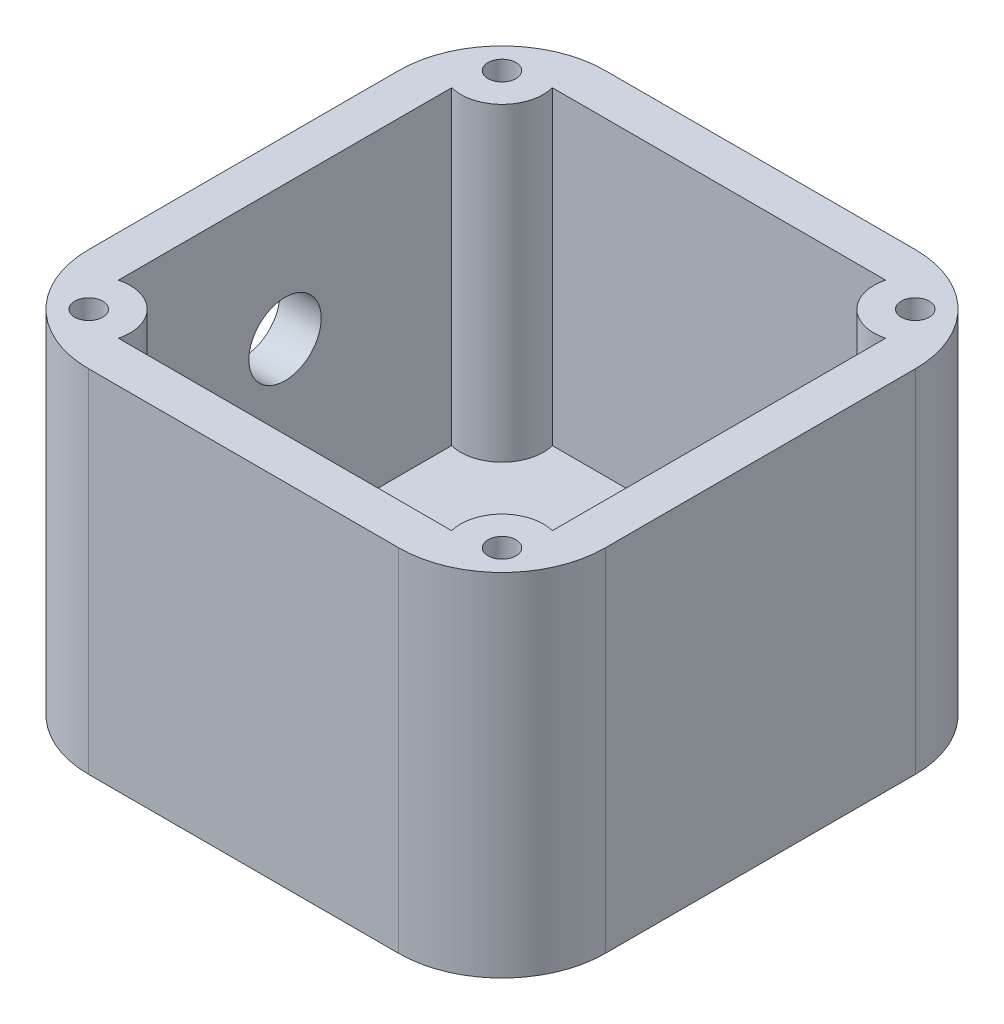
SolidWorks part; units mm, degrees
ref_plane "Front Plane" through (0, 0, 0) normal (0, 0, 1) x (1, 0, 0)
ref_plane "Top Plane" through (0, 0, 0) normal (0, 1, 0) x (1, 0, 0)
ref_plane "Right Plane" through (0, 0, 0) normal (1, 0, 0) x (0, 0, -1)
sketch "Sketch1" plane through (0, 0, 0) normal (0, 1, 0) x (1, 0, 0)
  line L1 (-21, 21) -> (21, 21)
  line L2 (-21, 21) -> (-21, -21)
  line L3 (-21, -21) -> (21, -21)
  line L4 (21, 21) -> (21, -21)
  line L5 (-21, 21) -> (21, -21) construction
  line L6 (-21, -21) -> (21, 21) construction
  point P0 (0, 0)
  dimension "D1" = 42
  dimension "D2" = 42
extrude "Boss-Extrude2" add sketch "Sketch1" along normal blind 30
shell "Shell1" thickness 4
sketch "Sketch2" plane through (0, -4, 0) normal (0, -1, 0) x (-1, 0, 0)
  circle A0 centre (0, 0) radius 6.75
  point P0 (0, 0)
sketch "Sketch3" plane through (0, 0, 0) normal (1, 0, 0) x (0, 0, -1)
  line L0 (-25, 30) -> (-25, -4) construction
  line L1 (-25, 30) -> (25, 30) construction
  circle A0 centre (0, 17) radius 3.5
  point P0 (-1.6703, 16.6909)
  point P7 (0, 30)
  dimension "D1" = 25
  dimension "D2" = 13
extrude "Cut-Extrude1" cut sketch "Sketch3" against normal blind 30
extrude "Cut-Extrude2" cut sketch "Sketch2" against normal blind 30
sketch "Sketch5" plane through (0, -4, 0) normal (0, -1, 0) x (-1, 0, 0)
  line L0 (25, -25) -> (-25, -25) construction
  line L1 (25, 25) -> (25, -25) construction
  line L2 (-25, -25) -> (-25, 25) construction
  line L3 (-25, 25) -> (25, 25) construction
  circle A0 centre (20, -20) radius 4
  circle A1 centre (-20, -20) radius 4
  circle A2 centre (-20, 20) radius 4
  circle A3 centre (20, 20) radius 4
  point P0 (20, 20)
  dimension "D1" = 5
  dimension "D3" = 5
  dimension "D2" = 5
  dimension "D4" = 5
extrude "Boss-Extrude3" add sketch "Sketch5" against normal blind 34
hole_wizard "#6-32 Tapped Hole6" positions "3DSketch6" profile "Sketch11" tap size "#6-32" standard "ANSI Inch"
sketch3d "3DSketch6"
  line L0 (-20, 30, -20) -> (-20, 0, -20) construction
  line L1 (20, 30, -20) -> (20, 0, -20) construction
  line L2 (20, 30, 20) -> (20, 0, 20) construction
  line L3 (-20, 30, 20) -> (-20, 0, 20) construction
  point P0 (-20, 30, -20)
  point P4 (20, 30, -20)
  point P8 (20, 30, 20)
  point P12 (-20, 30, 20)
sketch "Sketch11" plane through (-20, 30, -20) normal (1, 0, 0) x (0, 0, 1)
  line L0 (0, 0) -> (0, 11.7827)
  line L1 (0, 11.7827) -> (1.3525, 10.97)
  line L2 (1.3525, 10.97) -> (1.3525, 0)
  line L5 (1.3525, 0) -> (0, 0)
  line L10 (0, 11.7827) -> (-1.3525, 10.97) construction
  line L11 (0, -6.35) -> (0, 107.95) construction
  dimension "Tap Drill Dia." = 2.7051
  dimension "Tap Drill Depth" = 10.97
  dimension "Drill Angle" = 118
cosmetic thread "Hole Thread21" parameters "D1"=7.01, "D2"=3.5052
cosmetic thread "Hole Thread22" parameters "D1"=7.01, "D2"=3.5052
cosmetic thread "Hole Thread23" parameters "D1"=7.01, "D2"=3.5052
cosmetic thread "Hole Thread24" parameters "D1"=7.01, "D2"=3.5052
fillet "Fillet3" radius 10 4 edges at (-25, 13, 25) (25, 13, 25) (25, 13, -25) (-25, 13, -25)
